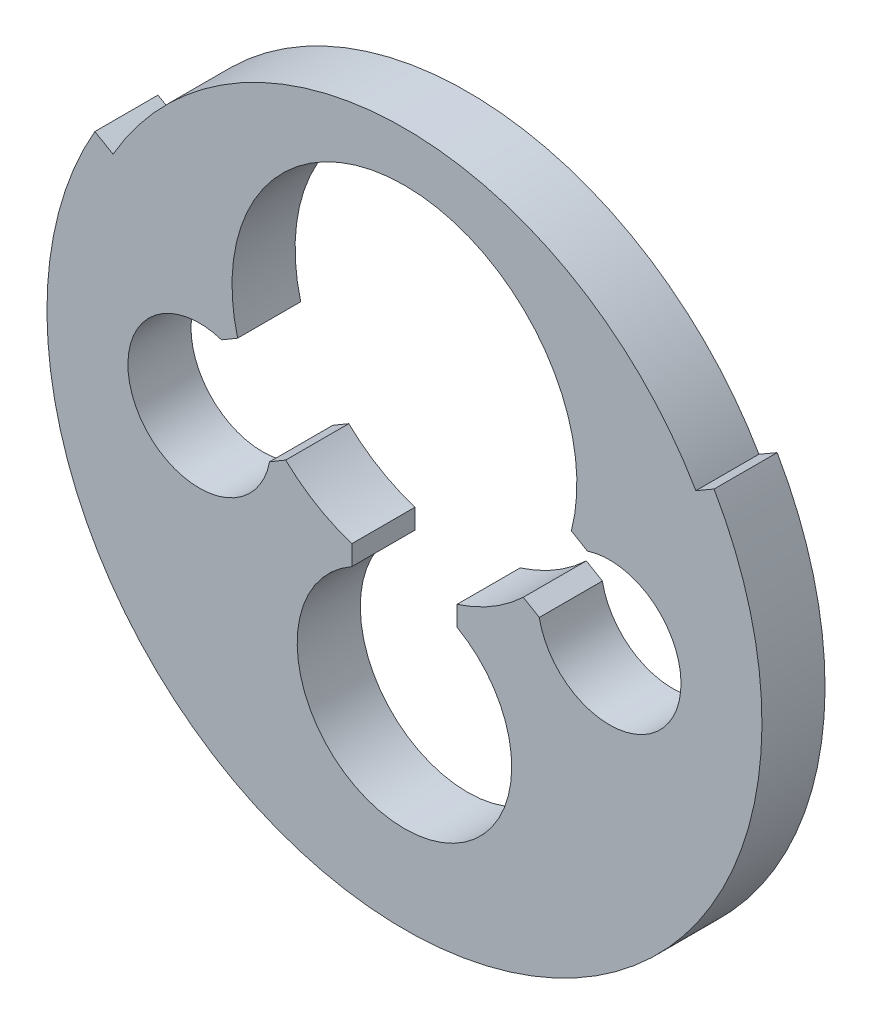
SolidWorks part; units mm, degrees
ref_plane "Спереди" through (0, 0, 0) normal (0, 0, 1) x (1, 0, 0)
ref_plane "Сверху" through (0, 0, 0) normal (0, 1, 0) x (1, 0, 0)
ref_plane "Справа" through (0, 0, 0) normal (1, 0, 0) x (0, 0, -1)
sketch "Эскиз1" plane through (0, 0, 0) normal (0, 0, 1) x (1, 0, 0)
  line L1 (0, 16) -> (0, -16) construction
  line L12 (-2.5, -2.3596) -> (-2.5, -3.3048)
  line L13 (2.5, -2.3596) -> (2.5, -3.3048)
  line L14 (-9.75, -0.3) -> (0, 5.45) construction
  line L15 (-8.6973, 2.9329) -> (-7.9351, 3.3825)
  line L16 (-6.4114, -0.9432) -> (-5.6491, -0.4937)
  line L17 (6.4114, -0.9432) -> (5.6491, -0.4937)
  line L18 (8.6973, 2.9329) -> (7.9351, 3.3825)
  arc A0 (7.9351, 3.3825) -> (-7.9351, 3.3825) centre (0, 5.45) ccw
  arc A1 (-5.6491, -0.4937) -> (-2.5, -2.3596) centre (0, 5.45) ccw
  arc A2 (-2.5, -3.3048) -> (2.5, -3.3048) centre (0, -7.75) ccw
  arc A3 (-8.6973, 2.9329) -> (-6.4114, -0.9432) centre (-9.75, -0.3) ccw
  arc A4 (8.6973, 2.9329) -> (6.4114, -0.9432) centre (9.75, -0.3) cw
  arc A5 (2.5, -2.3596) -> (5.6491, -0.4937) centre (0, 5.45) ccw
  arc A7 (5, -15.1987) -> (11.9295, 10.6624) centre (0, 0) ccw
  arc A8 (11.9295, 10.6624) -> (5, -15.1987) centre (0, 0) ccw
  dimension "D2" = 10.2
  dimension "D5" = 6.8
  dimension "D9" = 16.4
  dimension "D14" = 4.5
  dimension "D15" = 7.45
  dimension "D7" = 7.75
  dimension "D8" = 5.45
  dimension "D12" = 19.5
  dimension "D13" = 5
extrude "Бобышка-Вытянуть1" add sketch "Эскиз1" along normal mid plane 3
sketch "Sketch2" plane through (0, 0, 0) normal (0, 0, 1) x (1, 0, 0)
  line L0 (-16.9337, 1.5) -> (16.9337, 1.5) construction
  line L1 (-13.8564, 8) -> (-14.7224, 8.5)
  line L2 (13.8564, 8) -> (14.7224, 8.5)
  line L5 (0, 0) -> (0, 27.3636) construction
  line L6 (0, 0) -> (-2.5981, 1.5)
  line L7 (0, 0) -> (2.5981, 1.5)
  arc A0 (-13.8564, 8) -> (13.8564, 8) centre (0, 0) ccw
  arc A2 (-14.7224, 8.5) -> (-5, -16.2481) centre (0, 0) ccw
  arc A4 (-5, -16.2481) -> (14.7224, 8.5) centre (0, 0) ccw
  dimension "D1" = 17
  dimension "D2" = 1.5
  dimension "D3" = 60
  dimension "D4" = 60
extrude "Boss-Extrude3" add sketch "Sketch2" along normal up to surface and the other way up to surface up to face at (16, 0, 1.5) other way up to face at (16, 0, -1.5)
